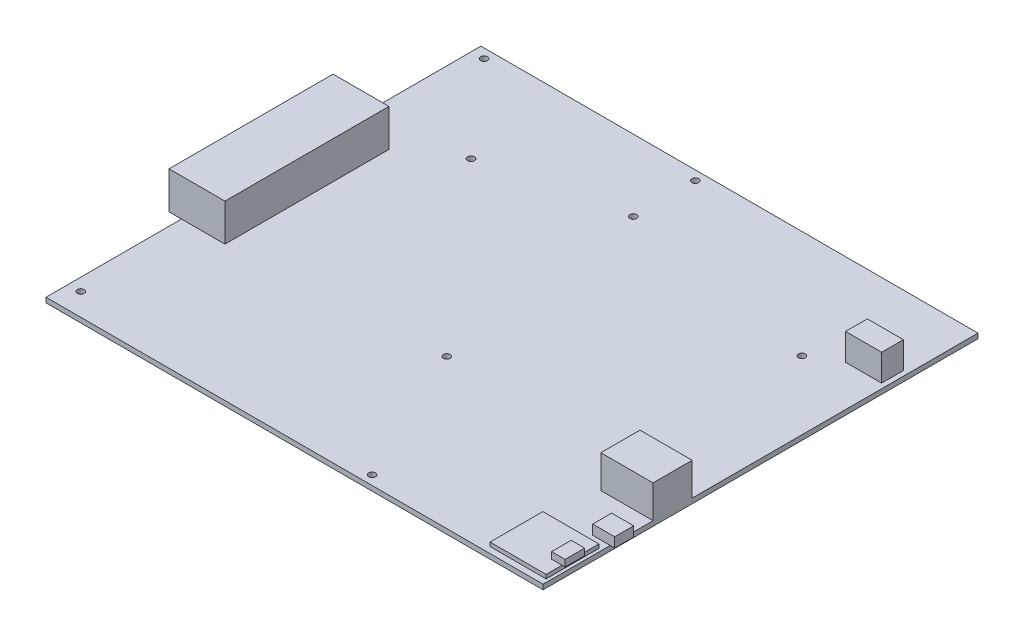
SolidWorks part; units mm, degrees
ref_plane "Front Plane" through (0, 0, 0) normal (0, 0, 1) x (1, 0, 0)
ref_plane "Top Plane" through (0, 0, 0) normal (0, 1, 0) x (1, 0, 0)
ref_plane "Right Plane" through (0, 0, 0) normal (1, 0, 0) x (0, 0, -1)
sketch "Sketch1" plane through (0, 0, 0) normal (0, 1, 0) x (1, 0, 0)
  line L1 (-101.6, -88.9) -> (101.6, -88.9)
  line L2 (-101.6, -88.9) -> (-101.6, 88.9)
  line L3 (-101.6, 88.9) -> (101.6, 88.9)
  line L4 (101.6, -88.9) -> (101.6, 88.9)
  line L5 (-101.6, -88.9) -> (101.6, 88.9) construction
  line L6 (-101.6, 88.9) -> (101.6, -88.9) construction
  point P0 (0, 0)
  dimension "D1" = 203.2
  dimension "D2" = 177.8
extrude "Boss-Extrude1" add sketch "Sketch1" along normal blind 2
sketch "Sketch3" plane through (0, 2, 0) normal (0, 1, 0) x (1, 0, 0)
  line L0 (101.6, -88.9) -> (101.6, 88.9) construction
  line L1 (101.6, -27.94) -> (80.25, -27.94)
  line L2 (101.6, -27.94) -> (101.6, -43.94)
  line L3 (101.6, -43.94) -> (80.25, -43.94)
  line L4 (80.25, -27.94) -> (80.25, -43.94)
  line L5 (-101.6, -88.9) -> (101.6, -88.9) construction
  dimension "D1" = 60.96
  dimension "D2" = 16
  dimension "D3" = 21.35
extrude "Boss-Extrude2" add sketch "Sketch3" along normal blind 13.4
sketch "Sketch2" plane through (0, 2, 0) normal (0, 1, 0) x (1, 0, 0)
  line L0 (-101.6, 88.9) -> (-101.6, -88.9) construction
  line L1 (101.6, 88.9) -> (-101.6, 88.9) construction
  line L2 (101.6, -88.9) -> (101.6, -43.94) construction
  line L3 (-101.6, -88.9) -> (101.6, -88.9) construction
  circle A0 centre (-96.52, 85.09) radius 1.397
  circle A1 centre (-10.16, 85.09) radius 1.397
  circle A2 centre (-10.16, 59.69) radius 1.397
  circle A3 centre (73.66, 44.831) radius 1.397
  circle A4 centre (-63.754, 46.99) radius 1.397
  circle A5 centre (1.27, -27.94) radius 1.397
  circle A6 centre (-96.52, -79.756) radius 1.397
  circle A7 centre (27.94, -85.09) radius 1.397
  circle A8 centre (-88.9, -30.48) radius 1.397
  circle A9 centre (-88.9, 30.48) radius 1.397
  dimension "D1" = 5.08
  dimension "D3" = 91.44
  dimension "D5" = 2.794
  dimension "D6" = 2.794
  dimension "D7" = 3.81
  dimension "D9" = 2.794
  dimension "D11" = 2.794
  dimension "D15" = 2.794
  dimension "D17" = 2.794
  dimension "D21" = 2.794
  dimension "D24" = 2.794
  dimension "D26" = 2.794
  dimension "D27" = 2.794
  dimension "D28" = 12.7
  dimension "D29" = 58.42
  dimension "D2" = 3.81
  dimension "D4" = 111.76
  dimension "D8" = 29.21
  dimension "D10" = 27.94
  dimension "D12" = 44.069
  dimension "D13" = 37.846
  dimension "D14" = 41.91
  dimension "D16" = 116.84
  dimension "D18" = 100.33
  dimension "D19" = 9.144
  dimension "D20" = 5.08
  dimension "D22" = 3.81
  dimension "D23" = 73.66
  dimension "D25" = 60.96
extrude "Cut-Extrude1" cut sketch "Sketch2" against normal through all both and the other way through all contours A0 | A1 | A2 | A4 | A5 | A3 | A9 | A8 | A7 | A6
sketch "Sketch4" plane through (0, 2, 0) normal (0, 1, 0) x (1, 0, 0)
  line L0 (-88.9, 30.48) -> (-88.9, 33.528) construction
  line L1 (-106.68, 33.528) -> (-83.82, 33.528)
  line L2 (-106.68, 33.528) -> (-106.68, -33.528)
  line L3 (-106.68, -33.528) -> (-83.82, -33.528)
  line L4 (-83.82, 33.528) -> (-83.82, -33.528)
  line L5 (-88.9, -30.48) -> (-88.9, -33.528) construction
  circle A1 centre (-88.9, 30.48) radius 1.397 construction
  point P12 (-88.9, 33.528)
  dimension "D1" = 22.86
  dimension "D2" = 5.08
  dimension "D3" = 67.056
extrude "Boss-Extrude3" add sketch "Sketch4" along normal blind 15.24
sketch "Sketch5" plane through (0, 2, 0) normal (0, 1, 0) x (1, 0, 0)
  line L0 (101.6, -27.94) -> (101.6, 88.9) construction
  line L1 (84.85, 51.5) -> (99.6, 51.5)
  line L2 (84.85, 51.5) -> (84.85, 60.4)
  line L3 (84.85, 60.4) -> (99.6, 60.4)
  line L4 (99.6, 51.5) -> (99.6, 60.4)
  line L5 (101.6, 88.9) -> (-101.6, 88.9) construction
  dimension "D1" = 14.75
  dimension "D2" = 8.9
  dimension "D3" = 2
  dimension "D4" = 28.5
extrude "Boss-Extrude4" add sketch "Sketch5" along normal blind 10.922 contours L1 L4 L3 L2
sketch "Sketch7" plane through (0, 2, 0) normal (0, 1, 0) x (1, 0, 0)
  line L0 (-101.6, -88.9) -> (101.6, -88.9) construction
  line L1 (94.45, -53.7) -> (103.45, -53.7)
  line L2 (94.45, -53.7) -> (94.45, -61.45)
  line L3 (94.45, -61.45) -> (103.45, -61.45)
  line L4 (103.45, -53.7) -> (103.45, -61.45)
  line L5 (101.6, -88.9) -> (101.6, -43.94) construction
  dimension "D1" = 35.2
  dimension "D2" = 7.75
  dimension "D3" = 9
  dimension "D4" = 1.85
extrude "Boss-Extrude5" add sketch "Sketch7" along normal blind 4
sketch "Sketch8" plane through (0, 2, 0) normal (0, 1, 0) x (1, 0, 0)
  line L0 (-101.6, -88.9) -> (101.6, -88.9) construction
  line L1 (77.45, -64.83) -> (100.35, -64.83)
  line L2 (77.45, -64.83) -> (77.45, -86.4)
  line L3 (77.45, -86.4) -> (100.35, -86.4)
  line L4 (100.35, -64.83) -> (100.35, -86.4)
  line L5 (101.6, -88.9) -> (101.6, -61.45) construction
  dimension "D1" = 21.57
  dimension "D2" = 22.9
  dimension "D3" = 2.5
  dimension "D4" = 1.25
extrude "Boss-Extrude6" add sketch "Sketch8" along normal blind 1.6
sketch "Sketch9" plane through (0, 3.6, 0) normal (0, 1, 0) x (1, 0, 0)
  line L0 (-101.6, -88.9) -> (101.6, -88.9) construction
  line L1 (96.1, -71.9) -> (101.6, -71.9)
  line L2 (96.1, -71.9) -> (96.1, -79.9)
  line L3 (96.1, -79.9) -> (101.6, -79.9)
  line L4 (101.6, -71.9) -> (101.6, -79.9)
  line L5 (101.6, -88.9) -> (101.6, -61.45) construction
  dimension "D1" = 8
  dimension "D2" = 5.5
  dimension "D3" = 17
extrude "Boss-Extrude7" add sketch "Sketch9" along normal blind 2.7
